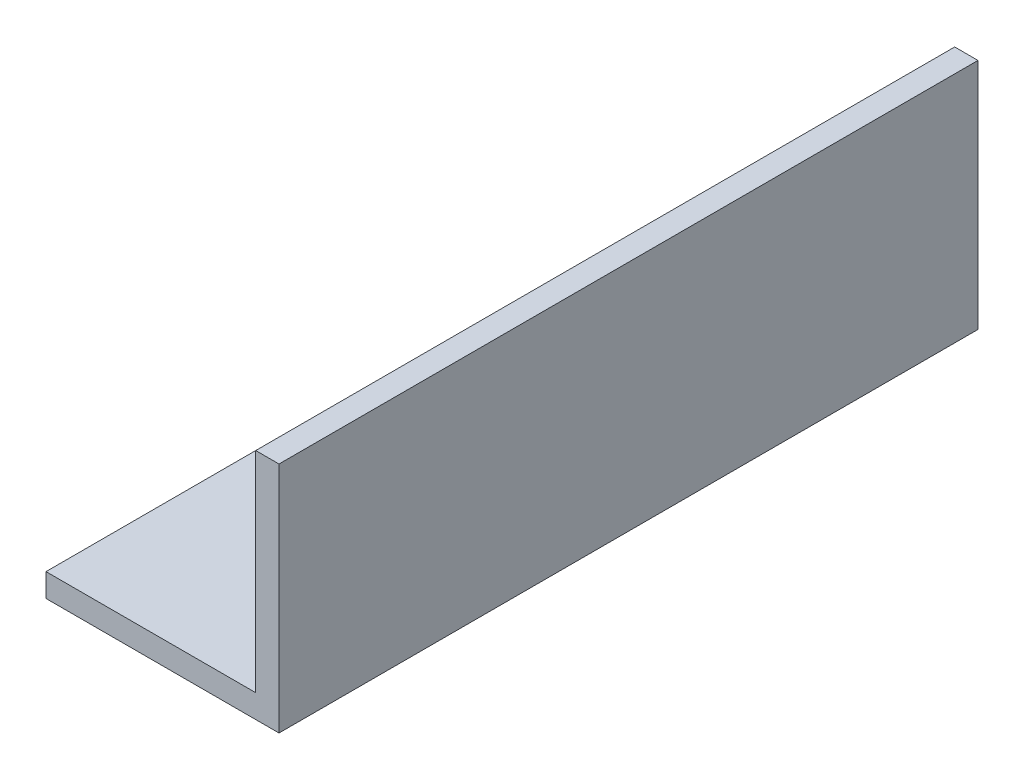
SolidWorks part; units mm, degrees
ref_plane "Front" through (0, 0, 0) normal (0, 0, 1) x (1, 0, 0)
ref_plane "Top" through (0, 0, 0) normal (0, 1, 0) x (1, 0, 0)
ref_plane "Right" through (0, 0, 0) normal (1, 0, 0) x (0, 0, -1)
sketch "Эскиз1" plane through (0, 0, 0) normal (0, 0, 1) x (1, 0, 0)
  line L0 (4, 0.5) -> (-5, 0.5)
  line L1 (5, -0.5) -> (-5, -0.5)
  line L2 (5, -0.5) -> (5, 0.5)
  line L3 (-5, 0) -> (5, 0) construction
  line L4 (-5, -0.5) -> (-5, 0.5)
  line L5 (5, -0.5) -> (-5, 0.5) construction
  line L6 (5, 0.5) -> (-5, -0.5) construction
  line L7 (4, 9.5) -> (5, 9.5)
  line L8 (4, 9.5) -> (4, 0.5)
  line L10 (5, 9.5) -> (5, 0.5)
  line L11 (4, 9.5) -> (5, 0.5) construction
  line L12 (4, 0.5) -> (5, 9.5) construction
  point P0 (0, 0)
  point P6 (4.5, 5)
  dimension "D1" = 10
  dimension "D2" = 10
  dimension "D3" = 1
extrude "Бобышка-Вытянуть1" add sketch "Эскиз1" along normal blind 30
hole_wizard "Диаметр отверстия Ø3.0 (3)1" positions "Эскиз3" profile "Эскиз2" hole size "Ø3.0" standard "Ansi Metric" end condition up to next
sketch "Эскиз3" plane through (0, 0.5, 0) normal (0, 1, 0) x (1, 0, 0)
  line L0 (-0.5, 0) -> (-0.5, -10) construction
  line L1 (4, 0) -> (-5, 0) construction
  line L2 (-0.5, -10) -> (-0.5, -20) construction
  line L3 (-0.5, -20) -> (-0.5, -30) construction
  line L4 (4, -30) -> (-5, -30) construction
  point P0 (-0.5, -10)
  point P18 (-0.5, -20)
  dimension "D1" = 10
sketch "Эскиз2" plane through (-0.5, 0.5, 10) normal (1, 0, 0) x (0, 0, 1)
  line L0 (0, 0) -> (0, 1)
  line L1 (0, 1) -> (1.5, 1)
  line L2 (1.5, 1) -> (1.5, 0)
  line L5 (1.5, 0) -> (0, 0)
  line L11 (0, -6.35) -> (0, 107.95) construction
  dimension "Диаметр сквозного отверстия" = 3
  dimension "Глубина сквозного отверстия" = 1
